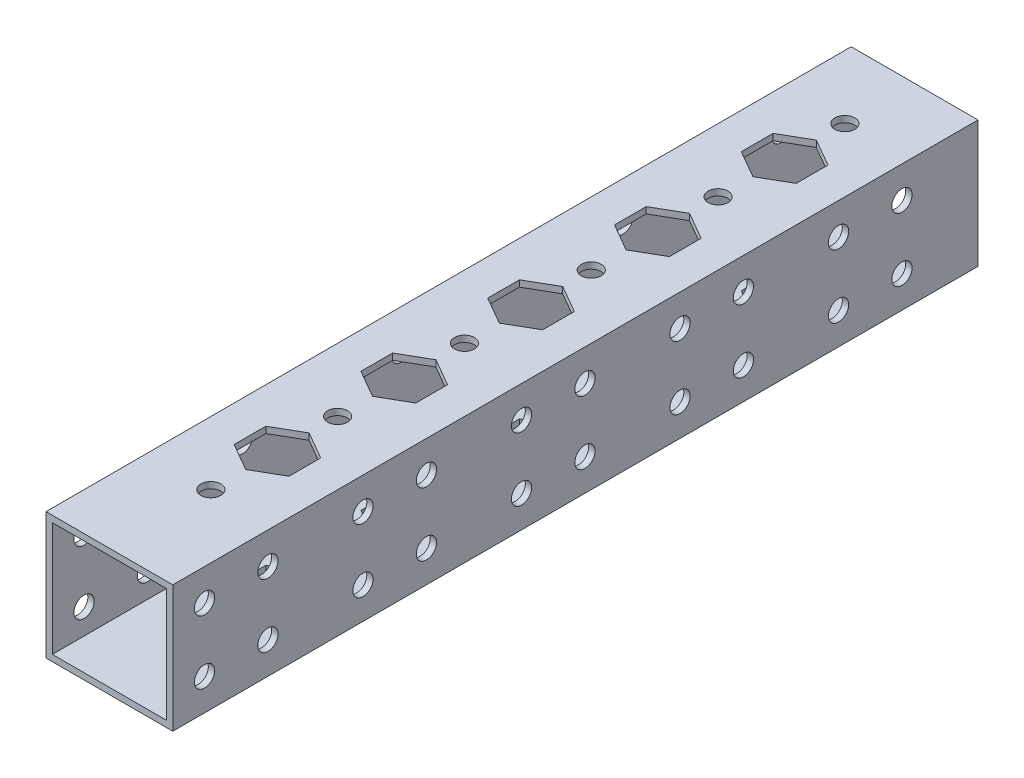
SolidWorks part; units mm, degrees
ref_plane "前视基准面" through (0, 0, 0) normal (0, 0, 1) x (1, 0, 0)
ref_plane "上视基准面" through (0, 0, 0) normal (0, 1, 0) x (1, 0, 0)
ref_plane "右视基准面" through (0, 0, 0) normal (1, 0, 0) x (0, 0, -1)
other "Configuration Table"
sketch "草图1" plane through (0, 0, 0) normal (0, 0, 1) x (1, 0, 0)
  line L1 (0, 0) -> (20, 0)
  line L2 (0, 0) -> (0, -20)
  line L3 (0, -20) -> (20, -20)
  line L4 (20, 0) -> (20, -20)
  dimension "D1" = 20
  dimension "D2" = 20
extrude "拉伸-薄壁1" add sketch "草图1" along normal blind 127 thin
sketch "草图2" plane through (0, -20, 0) normal (0, -1, 0) x (1, 0, 0)
  line L0 (0, 10) -> (20, 10) construction
  line L1 (20, 127) -> (20, 0) construction
  line L2 (0, 127) -> (0, 0) construction
  line L3 (10, 10) -> (10, 0) construction
  line L4 (0, 0) -> (20, 0) construction
  line L5 (10, 31) -> (10, 10) construction
  line L6 (10, 45.5) -> (5.6699, 43)
  line L7 (10, 25.5) -> (5.6699, 23)
  line L8 (5.6699, 23) -> (5.6699, 18)
  line L9 (5.6699, 18) -> (10, 15.5)
  line L10 (10, 15.5) -> (14.3301, 18)
  line L11 (14.3301, 18) -> (14.3301, 23)
  line L12 (14.3301, 23) -> (10, 25.5)
  line L13 (14.3301, 43) -> (10, 45.5)
  line L14 (14.3301, 38) -> (14.3301, 43)
  line L15 (10, 35.5) -> (14.3301, 38)
  line L16 (5.6699, 38) -> (10, 35.5)
  line L17 (5.6699, 43) -> (5.6699, 38)
  line L18 (10, 65.5) -> (5.6699, 63)
  line L19 (14.3301, 63) -> (10, 65.5)
  line L20 (14.3301, 58) -> (14.3301, 63)
  line L21 (10, 55.5) -> (14.3301, 58)
  line L22 (5.6699, 58) -> (10, 55.5)
  line L23 (5.6699, 63) -> (5.6699, 58)
  line L24 (10, 85.5) -> (5.6699, 83)
  line L25 (14.3301, 83) -> (10, 85.5)
  line L26 (14.3301, 78) -> (14.3301, 83)
  line L27 (10, 75.5) -> (14.3301, 78)
  line L28 (5.6699, 78) -> (10, 75.5)
  line L29 (5.6699, 83) -> (5.6699, 78)
  line L30 (10, 105.5) -> (5.6699, 103)
  line L31 (14.3301, 103) -> (10, 105.5)
  line L32 (14.3301, 98) -> (14.3301, 103)
  line L33 (10, 95.5) -> (14.3301, 98)
  line L34 (5.6699, 98) -> (10, 95.5)
  line L35 (5.6699, 103) -> (5.6699, 98)
  circle A4 centre (10, 11) radius 1.575
  circle A5 centre (10, 31) radius 1.575
  circle A6 centre (10, 51) radius 1.575
  circle A7 centre (10, 71) radius 1.575
  circle A8 centre (10, 91) radius 1.575
  circle A9 centre (10, 111) radius 1.575
  circle A15 centre (10, 20.5) radius 4.3301 construction
  circle A16 centre (10, 40.5) radius 4.3301 construction
  circle A17 centre (10, 60.5) radius 4.3301 construction
  circle A18 centre (10, 80.5) radius 4.3301 construction
  circle A19 centre (10, 100.5) radius 4.3301 construction
  dimension "D2" = 5
  dimension "D5" = 3.15
  dimension "D1" = 10
  dimension "D3" = 20
  dimension "D6" = 11
  dimension "D8" = 20
  dimension "D7" = 6
extrude "切除-拉伸1" cut sketch "草图2" against normal through all
sketch "草图3" plane through (0, 0, 0) normal (-1, 0, 0) x (0, 0, 1)
  line L0 (117, 0) -> (117, -20) construction
  line L1 (127, 0) -> (0, 0) construction
  line L2 (127, -20) -> (0, -20) construction
  line L3 (127, 0) -> (127, -20) construction
  line L4 (117, -10) -> (127, -10) construction
  circle A0 centre (122, -5) radius 1.6
  circle A1 centre (122, -15) radius 1.6
  circle A2 centre (112, -15) radius 1.6
  circle A3 centre (112, -5) radius 1.6
  circle A4 centre (97, -5) radius 1.6
  circle A5 centre (97, -15) radius 1.6
  circle A6 centre (87, -15) radius 1.6
  circle A7 centre (87, -5) radius 1.6
  circle A8 centre (72, -5) radius 1.6
  circle A9 centre (72, -15) radius 1.6
  circle A10 centre (62, -15) radius 1.6
  circle A11 centre (62, -5) radius 1.6
  circle A12 centre (47, -5) radius 1.6
  circle A13 centre (47, -15) radius 1.6
  circle A14 centre (37, -15) radius 1.6
  circle A15 centre (37, -5) radius 1.6
  circle A16 centre (22, -5) radius 1.6
  circle A17 centre (22, -15) radius 1.6
  circle A18 centre (12, -15) radius 1.6
  circle A19 centre (12, -5) radius 1.6
  dimension "D2" = 3.2
  dimension "D6" = 25
  dimension "D1" = 10
  dimension "D3" = 5
  dimension "D4" = 5
  dimension "D5" = 5
extrude "切除-拉伸2" cut sketch "草图3" against normal through all
